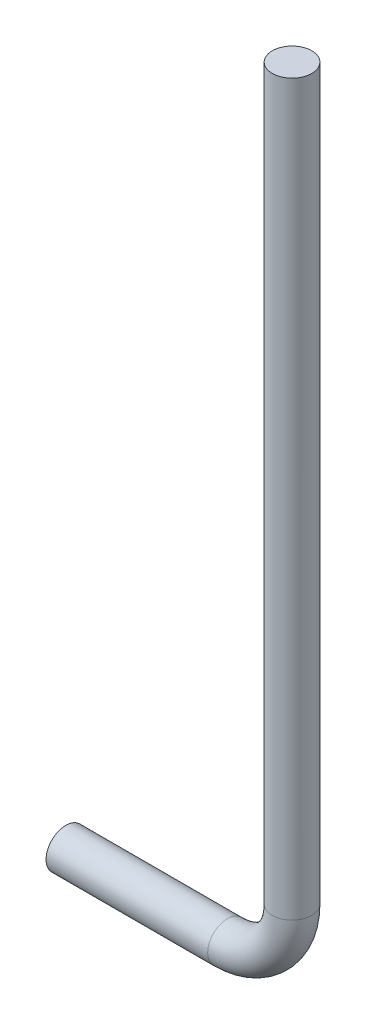
SolidWorks part; units mm, degrees
material "Copper"
ref_plane "Front Plane" through (0, 0, 0) normal (0, 0, 1) x (1, 0, 0)
ref_plane "Top Plane" through (0, 0, 0) normal (0, 1, 0) x (1, 0, 0)
ref_plane "Right Plane" through (0, 0, 0) normal (1, 0, 0) x (0, 0, -1)
ref_plane "Plane1" through (0, 0, -5) normal (0, 0, 1) x (1, 0, 0)
sketch "Sketch1" plane through (0, 0, -5) normal (0, 0, 1) x (1, 0, 0)
  line L0 (35, 89.5) -> (35, -14.5)
  line L1 (25, -24.5) -> (0, -24.5)
  arc A0 (35, -14.5) -> (25, -24.5) centre (25, -14.5) cw
  dimension "D1" = 10
  dimension "D2" = 35
  dimension "D3" = 35
  dimension "D4" = 24.5
  dimension "D5" = 104
sketch "Sketch2" plane through (0, 88.3, 0) normal (0, 1, 0) x (1, 0, 0)
  circle A0 centre (35, 5) radius 3.05
  dimension "D1" = 6.1
  dimension "D2" = 35
  dimension "D3" = 5
sweep "Sweep2" add profiles "Sketch2" path "Sketch1"
sketch "Sketch3" plane through (0, 88.3, 0) normal (0, 1, 0) x (1, 0, 0)
  circle A1 centre (35, 5) radius 3.05
  circle A2 centre (35, 5) radius 3.05
  dimension "D1" = 0
extrude "Boss-Extrude1" add sketch "Sketch3" along normal blind 10
